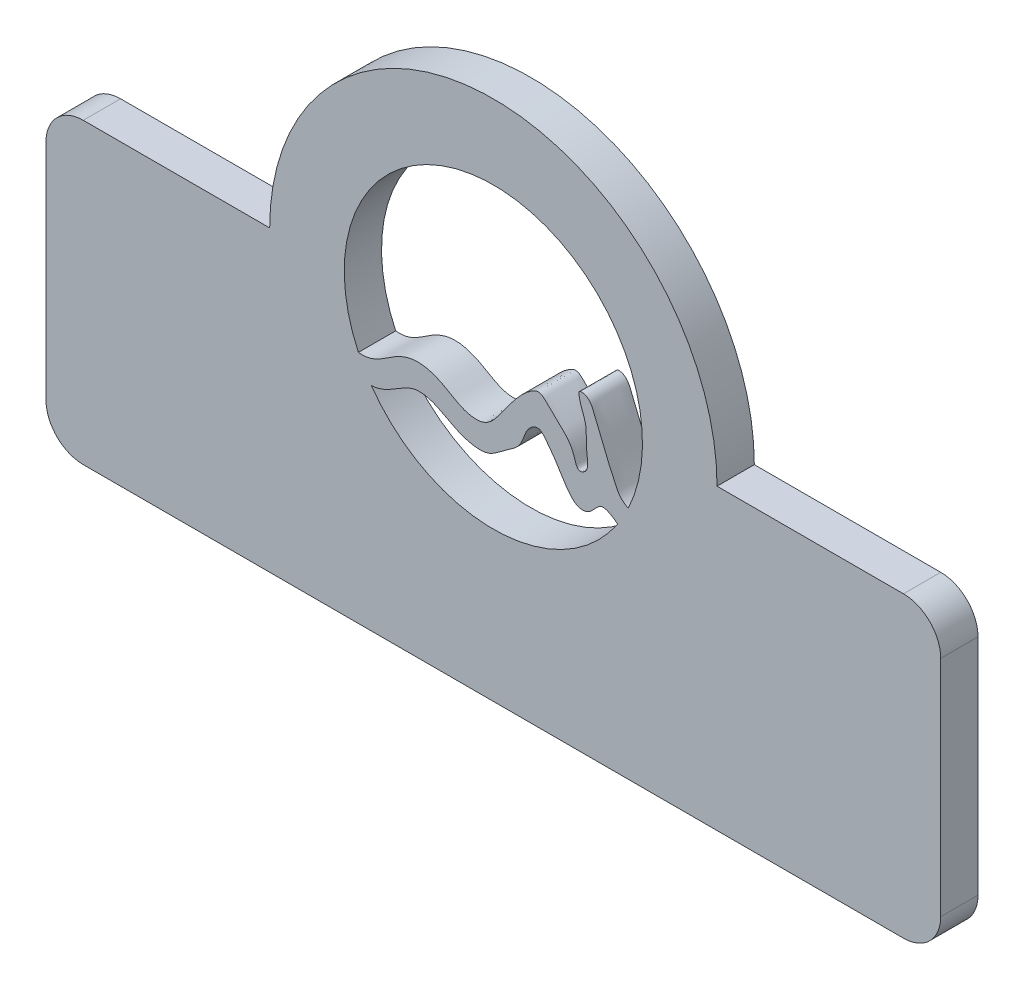
SolidWorks part; units mm, degrees
other "Camera1"
other "Camera2"
ref_plane "Front Plane" through (0, 0, 0) normal (0, 0, 1) x (1, 0, 0)
ref_plane "Top Plane" through (0, 0, 0) normal (0, 1, 0) x (1, 0, 0)
ref_plane "Right Plane" through (0, 0, 0) normal (1, 0, 0) x (0, 0, -1)
sketch "Sketch1" plane through (0, 0, 0) normal (0, 0, 1) x (1, 0, 0)
  line L0 (6.9108, 13.8216) -> (34.554, 13.8216) construction
  line L1 (6.9108, 13.8216) -> (34.554, 13.8216) construction
  line L2 (35.7853, 16.1395) -> (54.8353, 16.1395)
  line L3 (-21.3647, -9.2605) -> (54.8353, -9.2605)
  line L4 (-21.3647, -9.2605) -> (-21.3647, 16.1395)
  line L5 (-21.3647, 16.1395) -> (-2.3147, 16.1395)
  line L6 (54.8353, -9.2605) -> (54.8353, 16.1395)
  arc A0 (35.7853, 16.1395) -> (-2.3147, 16.1395) centre (16.7353, 16.1395) ccw
  point P10 (16.7353, -9.2605)
  dimension "D1" = 19.05
  dimension "D2" = 25.4
  dimension "D3" = 76.2
extrude "Boss-Extrude3" add sketch "Sketch1" along normal blind 3.175
sketch "Sketch2" plane through (0, 0, 0) normal (0, 0, 1) x (1, 0, 0)
  line L0 (6.9108, 13.8216) -> (34.554, 13.8216) construction
  line L1 (6.9108, 13.8216) -> (34.554, 13.8216) construction
  line L3 (-21.3647, -9.2605) -> (54.8353, -9.2605)
  line L4 (-21.3647, -9.2605) -> (-21.3647, 16.1395)
  line L5 (-21.3647, 16.1395) -> (4.0353, 16.1395)
  line L6 (54.8353, -9.2605) -> (54.8353, 16.1395)
  line L7 (29.4353, 16.1395) -> (54.8353, 16.1395)
  circle A0 centre (16.7353, 16.1395) radius 12.7
  spline S0 degree 3 poles (5.2422, 10.736) (6.7181, 10.5583) (7.9181, 12.0335) (10.4689, 12.7659) (12.4429, 12.0981) (14.04, 10.9311) (16.2264, 10.6186) (17.4992, 12.5179) (18.6877, 14.1015) (19.6579, 15.1072) (20.7366, 15.6711) (21.5924, 14.6574) (22.7186, 13.7475) (23.5698, 12.7033) (23.8626, 11.2746) (24.9534, 11.6978) (24.5407, 13.3498) (24.8083, 15.1398) (24.095, 16.3012) (23.9989, 17.3316) (24.934, 17.3133) (25.3682, 16.0395) (25.9915, 14.7265) (26.4068, 13.4846) (27.1285, 12.1461) (27.37, 11.104) (28.2285, 10.736) knots 0 0 0 0 0.103449 0.139242 0.205578 0.258602 0.299466 0.363653 0.418235 0.461509 0.476758 0.506043 0.548409 0.597042 0.622241 0.632003 0.675048 0.726967 0.779124 0.786559 0.795901 0.835777 0.878716 0.917237 0.938498 1 1 1 1
  spline S1 degree 3 poles (6.3413, 8.8418) (7.3529, 8.8928) (8.4397, 9.7204) (10.0783, 10.5483) (11.6016, 10.3368) (13.0104, 9.4793) (14.603, 8.7601) (16.3539, 8.6272) (17.6381, 9.777) (19.2522, 10.6455) (19.4083, 12.2512) (20.6019, 13.0206) (21.5067, 11.9378) (22.2898, 10.7945) (23.033, 9.4552) (23.9852, 8.5414) (25.1785, 8.7836) (25.8581, 10.2364) (27.0204, 9.3268) (27.3242, 9.1277) knots 0 0 0 0 0.111112 0.158804 0.207675 0.281443 0.349359 0.412439 0.469148 0.544608 0.609897 0.643349 0.67797 0.748785 0.815451 0.856727 0.888905 0.942631 1 1 1 1
  spline S2 degree 3 poles (15.5303, 10.8283) (14.8939, 12.0951) (14.4389, 13.9813) (14.3435, 16.7343) (15.2691, 18.2447) (16.5062, 19.5074) (18.14, 19.4662) (19.332, 18.7362) (19.9024, 17.9655) (20.6817, 17.4716) (21.4483, 18.509) (21.7334, 19.5035) (22.2913, 20.9391) (23.5141, 20.4969) (23.333, 19.7355) (23.6787, 18.9513) (24.8928, 19.8566) (24.7041, 21.7986) (25.937, 23.3158) (26.6866, 24.0301) knots 0 0 0 0 0.163827 0.228295 0.314759 0.363733 0.427294 0.487534 0.520272 0.543413 0.580046 0.637018 0.68948 0.715614 0.7546 0.768001 0.802503 0.870836 1 1 1 1
  dimension "D1" = 25.4
  dimension "D2" = 25.4
  dimension "D3" = 76.2
sketch "Sketch4" plane through (0, 0, 0) normal (0, 0, 1) x (1, 0, 0)
  line L0 (6.9108, 13.8216) -> (34.554, 13.8216) construction
  line L1 (6.9108, 13.8216) -> (34.554, 13.8216) construction
  line L3 (-21.3647, -9.2605) -> (54.8353, -9.2605)
  line L4 (-21.3647, -9.2605) -> (-21.3647, 16.1395)
  line L5 (-21.3647, 16.1395) -> (4.0353, 16.1395)
  line L6 (54.8353, -9.2605) -> (54.8353, 16.1395)
  line L7 (29.4353, 16.1395) -> (54.8353, 16.1395)
  circle A0 centre (16.7353, 16.1395) radius 12.7
  spline S0 degree 3 poles (5.2422, 10.736) (6.7181, 10.5583) (7.9181, 12.0335) (10.4689, 12.7659) (12.4429, 12.0981) (14.04, 10.9311) (16.2264, 10.6186) (17.4992, 12.5179) (18.6877, 14.1015) (19.6579, 15.1072) (20.7366, 15.6711) (21.5924, 14.6574) (22.7186, 13.7475) (23.5698, 12.7033) (23.8626, 11.2746) (24.9534, 11.6978) (24.5407, 13.3498) (24.8083, 15.1398) (24.095, 16.3012) (23.9989, 17.3316) (24.934, 17.3133) (25.3682, 16.0395) (25.9915, 14.7265) (26.4068, 13.4846) (27.1285, 12.1461) (27.37, 11.104) (28.2285, 10.736) knots 0 0 0 0 0.103449 0.139242 0.205578 0.258602 0.299466 0.363653 0.418235 0.461509 0.476758 0.506043 0.548409 0.597042 0.622241 0.632003 0.675048 0.726967 0.779124 0.786559 0.795901 0.835777 0.878716 0.917237 0.938498 1 1 1 1
  spline S1 degree 3 poles (6.3413, 8.8418) (7.3529, 8.8928) (8.4397, 9.7204) (10.0783, 10.5483) (11.6016, 10.3368) (13.0104, 9.4793) (14.603, 8.7601) (16.3539, 8.6272) (17.6381, 9.777) (19.2522, 10.6455) (19.4083, 12.2512) (20.6019, 13.0206) (21.5067, 11.9378) (22.2898, 10.7945) (23.033, 9.4552) (23.9852, 8.5414) (25.1785, 8.7836) (25.8581, 10.2364) (27.0204, 9.3268) (27.3242, 9.1277) knots 0 0 0 0 0.111112 0.158804 0.207675 0.281443 0.349359 0.412439 0.469148 0.544608 0.609897 0.643349 0.67797 0.748785 0.815451 0.856727 0.888905 0.942631 1 1 1 1
  spline S2 degree 3 poles (15.5303, 10.8283) (14.8939, 12.0951) (14.4389, 13.9813) (14.3435, 16.7343) (15.2691, 18.2447) (16.5062, 19.5074) (18.14, 19.4662) (19.332, 18.7362) (19.9024, 17.9655) (20.6817, 17.4716) (21.4483, 18.509) (21.7334, 19.5035) (22.2913, 20.9391) (23.5141, 20.4969) (23.333, 19.7355) (23.6787, 18.9513) (24.8928, 19.8566) (24.7041, 21.7986) (25.937, 23.3158) (26.6866, 24.0301) knots 0 0 0 0 0.163827 0.228295 0.314759 0.363733 0.427294 0.487534 0.520272 0.543413 0.580046 0.637018 0.68948 0.715614 0.7546 0.768001 0.802503 0.870836 1 1 1 1
  dimension "D1" = 25.4
  dimension "D2" = 25.4
  dimension "D3" = 76.2
extrude "Cut-Extrude2" cut sketch "Sketch2" against normal blind 3.175 from surface at 3.175 contours S0 S2 A0 | S1 A0 | S2 S0 A0 starting at face at (16.7353, 10.8478, 3.175)
fillet "Fillet1" radius 3.175 4 edges at (54.8353, 16.1395, 1.5875) (54.8353, -9.2605, 1.5875) (-21.3647, -9.2605, 1.5875) (-21.3647, 16.1395, 1.5875)
sketch "Sketch6" plane through (0, 0, 3.175) normal (0, 0, 1) x (1, 0, 0)
  line L0 (-21.3647, -6.0855) -> (54.8353, -6.0855)
sketch "Sketch5" plane through (0, 0, 3.175) normal (0, 0, 1) x (1, 0, 0)
  line L86 (-21.3647, -6.0855) -> (54.8353, -6.0855)
  line L87 (6.2741, 0.2645) -> (6.844, 0.2645)
  line L88 (6.844, 0.2645) -> (6.844, -4.0236)
  line L89 (3.8318, -5.5157) -> (4.1676, -5.0272)
  line L90 (6.2741, -3.96) -> (6.2741, 0.2645)
  line L91 (8.4722, 0.2645) -> (9.042, 0.2645)
  line L92 (9.042, 0.2645) -> (9.042, -3.5402)
  line L93 (11.9728, -3.5402) -> (11.9728, 0.2645)
  line L94 (11.9728, 0.2645) -> (12.5427, 0.2645)
  line L95 (12.5427, 0.2645) -> (12.5427, -3.5707)
  line L96 (8.4722, -3.5707) -> (8.4722, 0.2645)
  line L97 (13.5196, -4.8606) -> (14.0564, -4.5387)
  line L98 (17.1831, -0.6476) -> (16.6679, -1.0381)
  line L99 (17.8344, -0.3868) -> (17.8344, 0.2645)
  line L100 (17.8344, 0.2645) -> (21.1722, 0.2645)
  line L101 (21.1722, 0.2645) -> (21.1722, -0.3868)
  line L102 (21.1722, -0.3868) -> (19.7882, -0.3868)
  line L103 (19.7882, -0.3868) -> (19.7882, -6.0855)
  line L104 (19.7882, -6.0855) -> (19.2183, -6.0855)
  line L105 (19.2183, -6.0855) -> (19.2183, -0.3868)
  line L106 (19.2183, -0.3868) -> (17.8344, -0.3868)
  line L107 (22.1491, 0.2645) -> (22.719, 0.2645)
  line L108 (22.719, 0.2645) -> (22.719, -6.0855)
  line L109 (22.719, -6.0855) -> (22.1491, -6.0855)
  line L110 (22.1491, -6.0855) -> (22.1491, 0.2645)
  line L111 (24.3472, -6.0855) -> (24.3472, 0.2645)
  line L112 (24.3472, 0.2645) -> (24.4667, 0.2645)
  line L113 (24.4667, 0.2645) -> (28.6619, -4.7334)
  line L114 (28.6619, -4.7334) -> (28.6619, 0.2645)
  line L115 (28.6619, 0.2645) -> (29.2318, 0.2645)
  line L116 (29.2318, 0.2645) -> (29.2318, -6.0855)
  line L117 (29.2318, -6.0855) -> (29.102, -6.0855)
  line L118 (29.102, -6.0855) -> (24.917, -1.0992)
  line L119 (24.917, -1.0992) -> (24.917, -6.0855)
  line L120 (24.917, -6.0855) -> (24.3472, -6.0855)
  arc A0 (-21.3647, -6.0855) -> (-18.1897, -9.2605) centre (-18.1897, -6.0855) ccw construction
  spline S0 degree 3 poles (6.844, -4.0236) (6.8431, -4.1758) (6.8407, -4.3952) (6.8252, -4.6747) (6.809, -4.8563) (6.7873, -5.0188) (6.7626, -5.1633) (6.7326, -5.2888) (6.6875, -5.4296) (6.6135, -5.5841) (6.5022, -5.7509) (6.3639, -5.8969) (6.2037, -6.0236) (6.0202, -6.1245) (5.7425, -6.2241) (5.5164, -6.2488) (5.3633, -6.2484) knots 0 0 0 0 0.148542 0.214008 0.272995 0.326409 0.37388 0.41602 0.452126 0.518002 0.582367 0.647044 0.71333 0.780912 0.850395 1 1 1 1
  spline S1 degree 3 poles (5.3633, -6.2484) (5.2393, -6.2487) (5.0528, -6.2267) (4.8093, -6.1607) (4.6248, -6.0882) (4.4363, -5.9894) (4.1618, -5.808) (3.965, -5.6386) (3.8318, -5.5157) knots 0 0 0 0 0.213422 0.321685 0.433858 0.554081 0.687587 1 1 1 1
  spline S2 degree 3 poles (4.1676, -5.0272) (4.3123, -5.1306) (4.578, -5.2987) (4.8527, -5.4526) (4.9792, -5.5055) knots 0 0 0 0 0.564899 1 1 1 1
  spline S3 degree 3 poles (4.9792, -5.5055) (5.0473, -5.533) (5.1826, -5.5823) (5.3261, -5.5953) (5.3951, -5.5971) knots 0 0 0 0 0.515707 1 1 1 1
  spline S4 degree 3 poles (5.3951, -5.5971) (5.482, -5.5979) (5.6111, -5.5762) (5.7723, -5.5097) (5.8831, -5.4374) (5.9852, -5.3513) (6.0695, -5.2473) (6.1397, -5.1319) (6.182, -5.0228) (6.2089, -4.9232) (6.226, -4.8317) (6.241, -4.7247) (6.254, -4.6022) (6.2616, -4.4637) (6.2736, -4.2481) (6.2732, -4.0782) (6.2741, -3.96) knots 0 0 0 0 0.123196 0.184036 0.246964 0.310699 0.373268 0.436588 0.502125 0.539005 0.583255 0.634447 0.692676 0.75857 0.831659 1 1 1 1
  spline S5 degree 3 poles (9.042, -3.5402) (9.0419, -3.6424) (9.0416, -3.7878) (9.0459, -3.971) (9.0478, -4.0847) (9.052, -4.1822) (9.0561, -4.2807) (9.0614, -4.3465) (9.0675, -4.3848) knots 0 0 0 0 0.362605 0.516099 0.650038 0.765977 0.862374 1 1 1 1
  spline S6 degree 3 poles (9.0675, -4.3848) (9.0837, -4.5005) (9.1173, -4.6698) (9.2067, -4.8738) (9.2836, -5.0108) (9.3851, -5.1324) (9.5067, -5.2443) (9.654, -5.3422) (9.8177, -5.4318) (9.9942, -5.5037) (10.2324, -5.576) (10.4165, -5.5974) (10.538, -5.5971) knots 0 0 0 0 0.167766 0.244433 0.318135 0.391884 0.470068 0.553904 0.644339 0.736875 0.826168 1 1 1 1
  spline S7 degree 3 poles (10.538, -5.5971) (10.641, -5.5953) (10.7967, -5.5818) (10.9961, -5.5238) (11.1423, -5.4679) (11.2794, -5.3939) (11.4074, -5.3085) (11.5216, -5.2084) (11.6258, -5.0975) (11.7166, -4.9724) (11.8238, -4.7868) (11.8782, -4.6319) (11.9079, -4.526) knots 0 0 0 0 0.165303 0.247762 0.331528 0.41528 0.496366 0.577151 0.657783 0.739322 0.823793 1 1 1 1
  spline S8 degree 3 poles (11.9079, -4.526) (11.9217, -4.4764) (11.9343, -4.3922) (11.9486, -4.2697) (11.9569, -4.1542) (11.9648, -4.0232) (11.9715, -3.8167) (11.972, -3.6538) (11.9728, -3.5402) knots 0 0 0 0 0.155621 0.257802 0.373811 0.506402 0.655564 1 1 1 1
  spline S9 degree 3 poles (12.5427, -3.5707) (12.5427, -3.7056) (12.5382, -3.9034) (12.5211, -4.1599) (12.5035, -4.3373) (12.4802, -4.5039) (12.4543, -4.6612) (12.4213, -4.8081) (12.3828, -4.9457) (12.3388, -5.0766) (12.2817, -5.2009) (12.2175, -5.3223) (12.1412, -5.439) (12.0556, -5.5515) (11.9586, -5.659) (11.8535, -5.7634) (11.7386, -5.862) (11.6156, -5.9523) (11.4851, -6.0318) (11.348, -6.099) (11.2046, -6.1543) (11.055, -6.1958) (10.844, -6.2379) (10.6802, -6.2473) (10.5698, -6.2484) knots 0 0 0 0 0.107059 0.156978 0.203992 0.248492 0.290483 0.330489 0.367886 0.403858 0.440009 0.476295 0.512792 0.550485 0.588381 0.627645 0.667979 0.708433 0.748602 0.789088 0.829461 0.870371 0.912214 1 1 1 1
  spline S10 degree 3 poles (10.5698, -6.2484) (10.4501, -6.2465) (10.2724, -6.2389) (10.0429, -6.198) (9.8791, -6.1596) (9.7231, -6.1066) (9.5727, -6.0448) (9.4305, -5.9688) (9.2943, -5.8843) (9.1676, -5.7892) (9.0513, -5.6855) (8.9452, -5.5749) (8.8511, -5.4563) (8.7675, -5.3304) (8.6704, -5.1513) (8.6153, -5.0074) (8.5854, -4.9089) knots 0 0 0 0 0.139644 0.206317 0.271373 0.335418 0.398076 0.460608 0.52297 0.584716 0.644895 0.704291 0.762998 0.821087 0.880104 1 1 1 1
  spline S11 degree 3 poles (8.5854, -4.9089) (8.5632, -4.8361) (8.5382, -4.7153) (8.5155, -4.5407) (8.4982, -4.3826) (8.4881, -4.206) (8.4755, -3.9334) (8.4707, -3.7196) (8.4722, -3.5707) knots 0 0 0 0 0.169465 0.274335 0.39211 0.523687 0.668365 1 1 1 1
  spline S12 degree 3 poles (14.0564, -4.5387) (14.1494, -4.7001) (14.2962, -4.9264) (14.5269, -5.1827) (14.6992, -5.3331) (14.8775, -5.4513) (15.1224, -5.5628) (15.3199, -5.5974) (15.4506, -5.5971) knots 0 0 0 0 0.304646 0.438547 0.562322 0.677433 0.786897 1 1 1 1
  spline S13 degree 3 poles (15.4506, -5.5971) (15.561, -5.5981) (15.7255, -5.5787) (15.9369, -5.5175) (16.0868, -5.4526) (16.2267, -5.3739) (16.3493, -5.279) (16.4554, -5.1726) (16.5421, -5.054) (16.6086, -4.9264) (16.6769, -4.7522) (16.6929, -4.6124) (16.6946, -4.5209) knots 0 0 0 0 0.18093 0.270088 0.360156 0.448343 0.532666 0.613834 0.693982 0.772716 0.849335 1 1 1 1
  spline S14 degree 3 poles (16.6946, -4.5209) (16.6952, -4.4133) (16.6519, -4.1889) (16.5361, -3.9923) (16.4669, -3.8976) knots 0 0 0 0 0.477158 1 1 1 1
  spline S15 degree 3 poles (16.4669, -3.8976) (16.4084, -3.8204) (16.3094, -3.7034) (16.1558, -3.554) (16.0217, -3.4287) (15.8691, -3.3012) (15.6389, -3.1133) (15.4514, -2.9783) (15.3221, -2.8851) knots 0 0 0 0 0.18953 0.299198 0.418926 0.548376 0.688136 1 1 1 1
  spline S16 degree 3 poles (15.3221, -2.8851) (15.1936, -2.7952) (15.0137, -2.6617) (14.7892, -2.488) (14.649, -2.375) (14.5286, -2.2724) (14.4034, -2.1603) (14.3254, -2.0755) (14.2816, -2.0214) knots 0 0 0 0 0.347082 0.495568 0.628357 0.74552 0.845831 1 1 1 1
  spline S17 degree 3 poles (14.2816, -2.0214) (14.2254, -1.9487) (14.1471, -1.8371) (14.0635, -1.678) (14.0149, -1.5574) (13.9741, -1.4354) (13.9371, -1.2686) (13.9262, -1.1403) (13.9267, -1.0546) knots 0 0 0 0 0.262559 0.388264 0.512667 0.633722 0.755394 1 1 1 1
  spline S18 degree 3 poles (13.9267, -1.0546) (13.9263, -0.9218) (13.9514, -0.7241) (14.036, -0.4749) (14.1235, -0.3002) (14.2365, -0.1406) (14.3672, 0.0057) (14.5229, 0.1286) (14.6937, 0.2361) (14.8806, 0.3201) (15.1438, 0.4056) (15.3526, 0.4255) (15.4913, 0.4273) knots 0 0 0 0 0.16578 0.24628 0.327461 0.408797 0.489715 0.571376 0.655523 0.741019 0.826547 1 1 1 1
  spline S19 degree 3 poles (15.4913, 0.4273) (15.6399, 0.4275) (15.8631, 0.4002) (16.1445, 0.301) (16.3141, 0.2173) (16.4468, 0.1336) (16.5479, 0.0574) (16.6505, -0.0304) (16.7552, -0.1299) (16.8603, -0.2422) (17.0075, -0.4126) (17.1139, -0.5502) (17.1831, -0.6476) knots 0 0 0 0 0.213252 0.31883 0.426794 0.483646 0.543604 0.608308 0.677127 0.750686 0.828713 1 1 1 1
  spline S20 degree 3 poles (16.6679, -1.0381) (16.6089, -0.9602) (16.5193, -0.851) (16.4002, -0.7141) (16.3158, -0.6283) (16.237, -0.5508) (16.1606, -0.4845) (16.0876, -0.4287) (15.9956, -0.3691) (15.88, -0.3101) (15.6853, -0.2427) (15.5308, -0.2246) (15.4277, -0.224) knots 0 0 0 0 0.189629 0.274184 0.352183 0.423199 0.488551 0.548473 0.60144 0.701198 0.799592 1 1 1 1
  spline S21 degree 3 poles (15.4277, -0.224) (15.3014, -0.2222) (15.116, -0.2492) (14.8943, -0.3497) (14.7554, -0.4518) (14.6399, -0.5729) (14.5273, -0.7593) (14.4967, -0.921) (14.4965, -1.0279) knots 0 0 0 0 0.275903 0.402371 0.528414 0.650356 0.765895 1 1 1 1
  spline S22 degree 3 poles (14.4965, -1.0279) (14.4944, -1.0963) (14.5099, -1.1977) (14.5442, -1.331) (14.5847, -1.4307) (14.6407, -1.5313) (14.7445, -1.6777) (14.8436, -1.7795) (14.915, -1.8484) knots 0 0 0 0 0.214746 0.322939 0.434116 0.553412 0.686073 1 1 1 1
  spline S23 degree 3 poles (14.915, -1.8484) (14.9477, -1.8783) (15.0073, -1.9274) (15.1021, -1.998) (15.199, -2.0717) (15.3151, -2.1571) (15.5074, -2.2939) (15.6599, -2.4042) (15.7686, -2.4806) knots 0 0 0 0 0.124952 0.218094 0.333502 0.468789 0.624938 1 1 1 1
  spline S24 degree 3 poles (15.7686, -2.4806) (15.9022, -2.5774) (16.0952, -2.7193) (16.333, -2.9164) (16.488, -3.055) (16.6275, -3.1884) (16.7499, -3.3182) (16.8563, -3.4436) (16.971, -3.6043) (17.0879, -3.8016) (17.2204, -4.1179) (17.2644, -4.3664) (17.2645, -4.5298) knots 0 0 0 0 0.187773 0.272396 0.351321 0.424335 0.491909 0.554233 0.611268 0.716348 0.81454 1 1 1 1
  spline S25 degree 3 poles (17.2645, -4.5298) (17.2662, -4.6427) (17.2478, -4.8098) (17.194, -5.0259) (17.1341, -5.1799) (17.0609, -5.3301) (16.9681, -5.4723) (16.8605, -5.6099) (16.7371, -5.739) (16.602, -5.8576) (16.4592, -5.963) (16.3086, -6.051) (16.1508, -6.1227) (15.9859, -6.1788) (15.7535, -6.234) (15.5724, -6.2488) (15.4506, -6.2484) knots 0 0 0 0 0.121775 0.18092 0.240256 0.300114 0.361146 0.423501 0.488669 0.553954 0.617581 0.680238 0.742187 0.804663 0.868259 1 1 1 1
  spline S26 degree 3 poles (15.4506, -6.2484) (15.3552, -6.2489) (15.2136, -6.2374) (15.0282, -6.2062) (14.8946, -6.1697) (14.7639, -6.1252) (14.6366, -6.0706) (14.5127, -6.005) (14.3915, -5.9301) (14.2733, -5.8429) (14.1591, -5.7414) (14.0453, -5.6283) (13.9352, -5.5005) (13.8266, -5.3602) (13.6825, -5.1489) (13.5834, -4.9789) (13.5196, -4.8606) knots 0 0 0 0 0.113696 0.169178 0.224159 0.27872 0.333794 0.389241 0.445822 0.503704 0.564294 0.627975 0.695038 0.765373 0.839611 1 1 1 1
